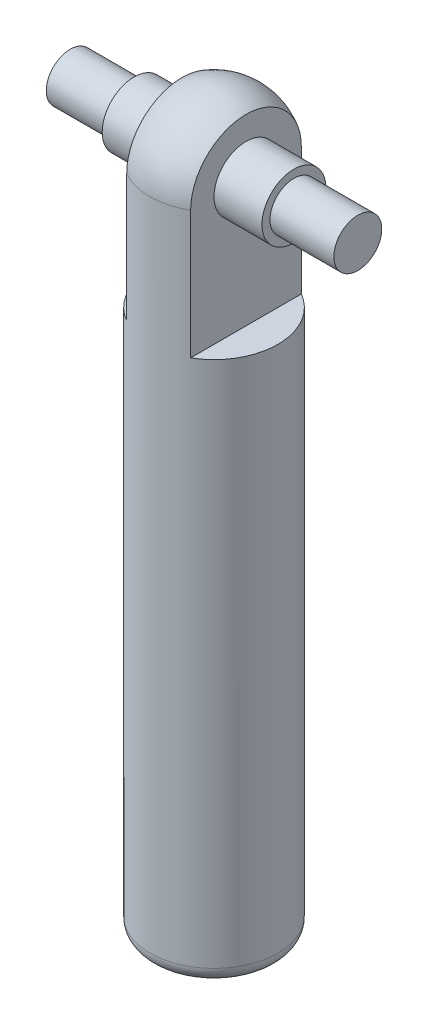
SolidWorks part; units mm, degrees
ref_plane "Front Plane" through (0, 0, 0) normal (0, 0, 1) x (1, 0, 0)
ref_plane "Top Plane" through (0, 0, 0) normal (0, 1, 0) x (1, 0, 0)
ref_plane "Right Plane" through (0, 0, 0) normal (1, 0, 0) x (0, 0, -1)
sketch "Sketch2" plane through (0, 0, 0) normal (0, 0, 1) x (1, 0, 0)
  line L0 (4, 0) -> (4, -41)
  line L1 (3, -42) -> (0, -42)
  line L2 (0, -42) -> (0, 4)
  arc A0 (0, 4) -> (4, 0) centre (0, 0) cw
  arc A1 (4, -41) -> (3, -42) centre (3, -41) cw
  point P8 (4, -42)
  dimension "D2" = 4
  dimension "D3" = 1
  dimension "D1" = 42
revolve "Revolve1" add sketch "Sketch2" angle 360 about L2
sketch "Sketch3" plane through (0, 0, 0) normal (1, 0, 0) x (0, 0, -1)
  circle A0 centre (0, 0) radius 2
  dimension "D1" = 4
extrude "Cut-Extrude1" cut sketch "Sketch3" against normal through all both and the other way through all
sketch "Sketch4" plane through (0, 0, 0) normal (0, 1, 0) x (1, 0, 0)
  line L0 (2, -3.4641) -> (2, 3.4641)
  line L1 (-2, 3.4641) -> (-2, -3.4641)
  arc A0 (3.4641, 2) -> (-3.4641, 2) centre (0, 0) ccw construction
  arc A1 (-3.4641, -2) -> (3.4641, -2) centre (0, 0) ccw construction
  arc A2 (-2, 3.4641) -> (-2, -3.4641) centre (0, 0) ccw
  arc A3 (2, -3.4641) -> (2, 3.4641) centre (0, 0) ccw
  dimension "D1" = 4
extrude "Cut-Extrude3" cut sketch "Sketch4" against normal blind 12 from offset 4 contours L0 A3 | L1 A2
sketch "Sketch5" plane through (0, 0, 0) normal (0, 0, 1) x (1, 0, 0)
  line L0 (-9, 0) -> (9, 0)
  line L1 (9, 0) -> (9, 1.5)
  line L2 (9, 1.5) -> (5, 1.5)
  line L3 (5, 1.5) -> (5, 2)
  line L4 (5, 2) -> (-5, 2)
  line L5 (-5, 2) -> (-5, 1.5)
  line L6 (-5, 1.5) -> (-9, 1.5)
  line L7 (-9, 1.5) -> (-9, 0)
  point P3 (0, 0)
  point P10 (0, 2)
  dimension "D1" = 10
  dimension "D2" = 4
  dimension "D3" = 2
  dimension "D4" = 1.5
  dimension "D5" = 1.5
revolve "Revolve2" add sketch "Sketch5" angle 360 about L0
cosmetic thread "Cosmetic Thread1" parameters "D2"=2.439
cosmetic thread "Cosmetic Thread2" parameters "D2"=2.439
